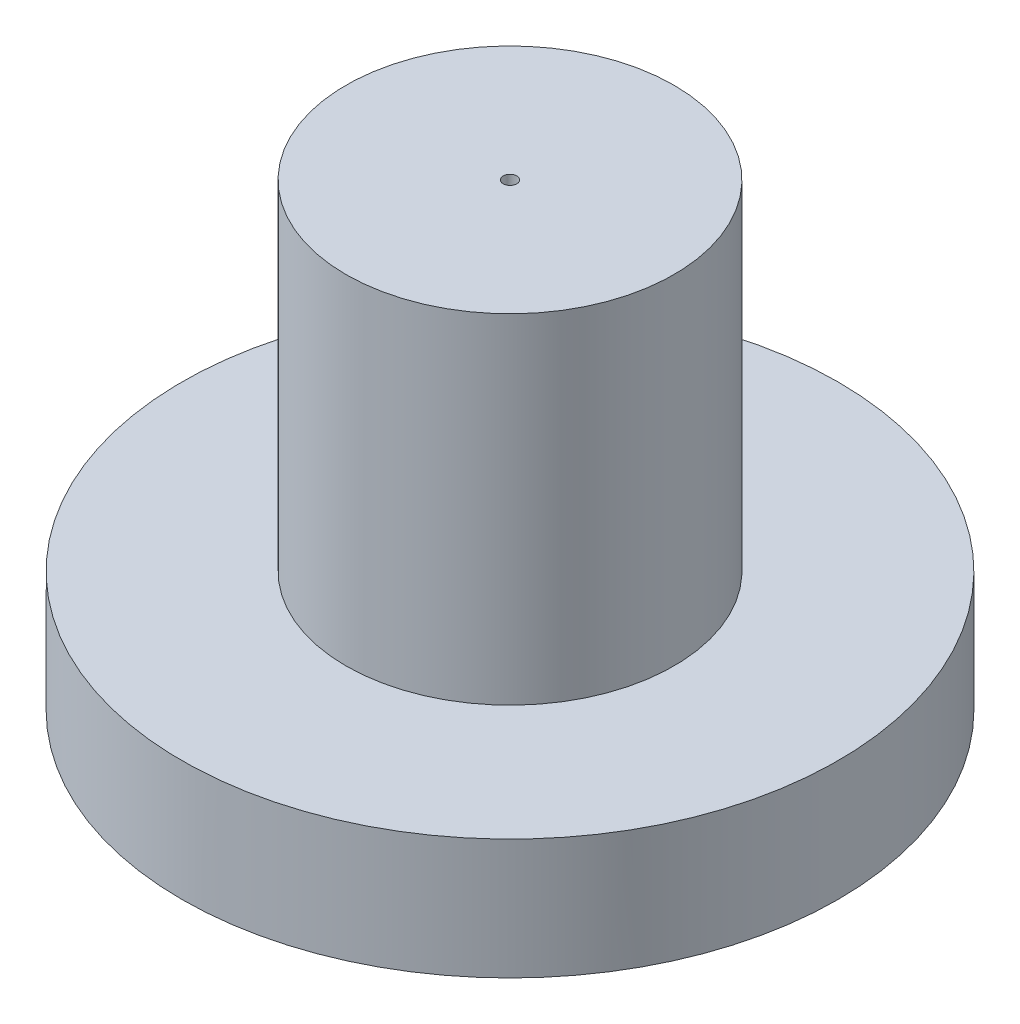
SolidWorks part; units mm, degrees
ref_plane "Front Plane" through (0, 0, 0) normal (0, 0, 1) x (1, 0, 0)
ref_plane "Top Plane" through (0, 0, 0) normal (0, 1, 0) x (1, 0, 0)
ref_plane "Right Plane" through (0, 0, 0) normal (1, 0, 0) x (0, 0, -1)
sketch "Sketch1" plane through (0, 0, 0) normal (0, 0, 1) x (1, 0, 0)
  line L0 (0, 0) -> (0, 15.7171)
  line L1 (0, 15.7171) -> (6, 15.7171)
  line L2 (6, 15.7171) -> (6, 3.3171)
  line L3 (6, 3.3171) -> (12, 3.3171)
  line L4 (12, 3.3171) -> (12, -1.0829)
  line L5 (12, -1.0829) -> (9.8, -1.6829)
  arc A0 (0, 0) -> (9.8, -1.6829) centre (0, -29.3755) cw
  point P8 (0, 0)
  point P10 (17.4457, -6.4596)
  point P11 (9.0027, -4.1732)
  point P12 (0, 0)
  point P13 (0, 0)
  point P14 (9.8, -1.9181)
  point P15 (9.8, -1.6829)
  dimension "D1" = 12.4
  dimension "D2" = 12
  dimension "D3" = 6
  dimension "D4" = 4.4
  dimension "D5" = 5
  dimension "D6" = 2.2
revolve "Revolve1" add sketch "Sketch1" angle 360 about L0
sketch "Sketch3" plane through (0, 0, 0) normal (0, 0, 1) x (1, 0, 0)
  line L0 (0, 0) -> (0, -1.1543)
  arc A0 (9.8, -1.6829) -> (-9.8, -1.6829) centre (0, -29.3755) ccw construction
  arc A1 (9.8, -1.6829) -> (-9.8, -1.6829) centre (0, -29.3755) ccw
  arc A2 (1.5, -0.0383) -> (0, -1.1543) centre (0, 0.4118) cw
  point P8 (0, -0.5696)
  point P9 (0.0441, -1.382)
  point P10 (0, 0)
  point P11 (1.1899, 0)
  point P12 (2.1371, -0.0778)
  point P13 (0, -0.9568)
  point P14 (0, -0.6055)
  point P15 (0, -0.5371)
  point P16 (0, -0.6763)
  dimension "D1" = 1.5
revolve "Revolve2" add sketch "Sketch3" angle 360 about L0
sketch "Sketch4" plane through (0, 15.7171, 0) normal (0, 1, 0) x (1, 0, 0)
  circle A0 centre (0, 0) radius 0.25
  dimension "D1" = 0.5
extrude "Cut-Extrude1" cut sketch "Sketch4" against normal up to next
sketch "Sketch5" plane through (0, 0, 0) normal (0, 0, 1) x (1, 0, 0)
  line L0 (0, 0) -> (0, -1.7135)
  line L1 (0, 0) -> (0, 15.7171) construction
  arc A0 (9.8, -1.6829) -> (0, 0) centre (0, -29.3755) ccw construction
  arc A1 (9.8, -1.6829) -> (0, 0) centre (0, -29.3755) ccw
  arc A2 (4, -0.2736) -> (0, -1.7135) centre (0, 4.5624) cw
  point P6 (2.7628, -0.1302)
  point P9 (0.0511, -1.3762)
  point P10 (0, -1.0269)
  dimension "D1" = 4
revolve "Revolve3" add sketch "Sketch5" angle 360 about L0
sketch "Sketch7" plane through (0, 0, 0) normal (0, 0, 1) x (1, 0, 0)
  line L0 (0, 0) -> (0, -4.1352)
  line L1 (0, 0) -> (0, 15.7171) construction
  arc A0 (9.8, -1.6829) -> (0, 0) centre (0, -29.3755) ccw construction
  arc A1 (9.8, -1.6829) -> (0, 0) centre (0, -29.3755) ccw
  arc A2 (9.8, -1.6829) -> (0, -4.1352) centre (0, 16.6729) cw
  point P5 (0, -3.5272)
  point P8 (0, -7.8606)
  point P9 (0.0792, -7.8606)
  point P10 (0, -4.1352)
revolve "Revolve4" add sketch "Sketch7" angle 360 about L0
